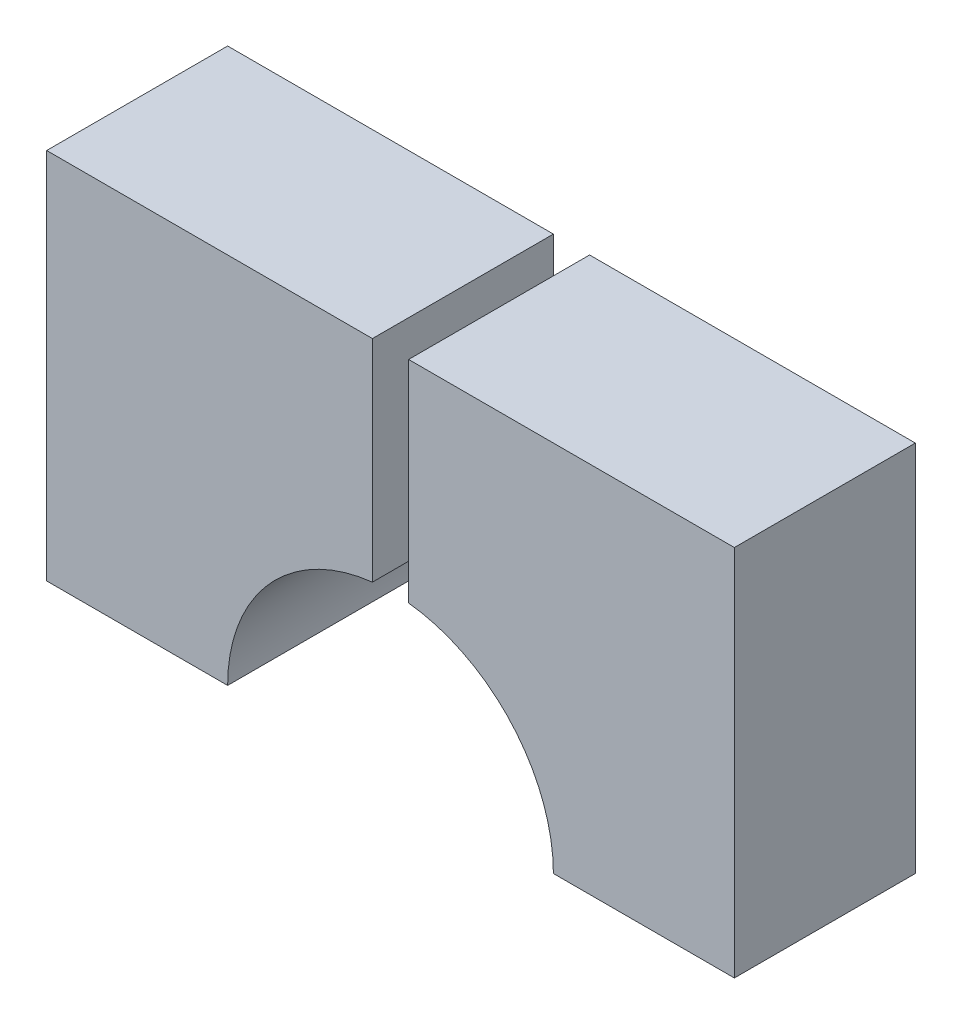
SolidWorks part; units mm, degrees
ref_plane "Front Plane" through (0, 0, 0) normal (0, 0, 1) x (1, 0, 0)
ref_plane "Top Plane" through (0, 0, 0) normal (0, 1, 0) x (1, 0, 0)
ref_plane "Right Plane" through (0, 0, 0) normal (1, 0, 0) x (0, 0, -1)
sketch "Sketch2" plane through (0, 0, 0) normal (0, 0, 1) x (1, 0, 0)
  line L0 (190, -505.6503) -> (-190, -505.6503)
  line L1 (190, -505.6503) -> (190, -299.6503)
  line L2 (0, -505.6503) -> (0, -299.6503)
  line L3 (10, -505.6503) -> (10, -299.6503)
  line L4 (190, -299.6503) -> (0, -299.6503)
  line L5 (322.5, -299.6503) -> (-322.5, -299.6503) construction
  line L6 (322.5, -299.6503) -> (-322.5, -299.6503)
  line L7 (322.5, -299.6503) -> (-322.5, -299.6503)
  arc A0 (88.6225, -521.3364) -> (-88.6225, -489.9643) centre (0, -505.6503) ccw construction
  arc A1 (88.6225, -521.3364) -> (-88.6225, -489.9643) centre (0, -505.6503) ccw
  circle A2 centre (0, -505.6503) radius 90
  point P4 (90, -505.6503)
  point P8 (0, -505.6503)
  dimension "D1" = 100
  dimension "D2" = 10
extrude "Boss-Extrude1" add sketch "Sketch2" against normal blind 100 from offset 30 offset against normal yes
mirror "Mirror3" about plane through (0, 0, 0) normal (1, 0, 0) of bodies 101
